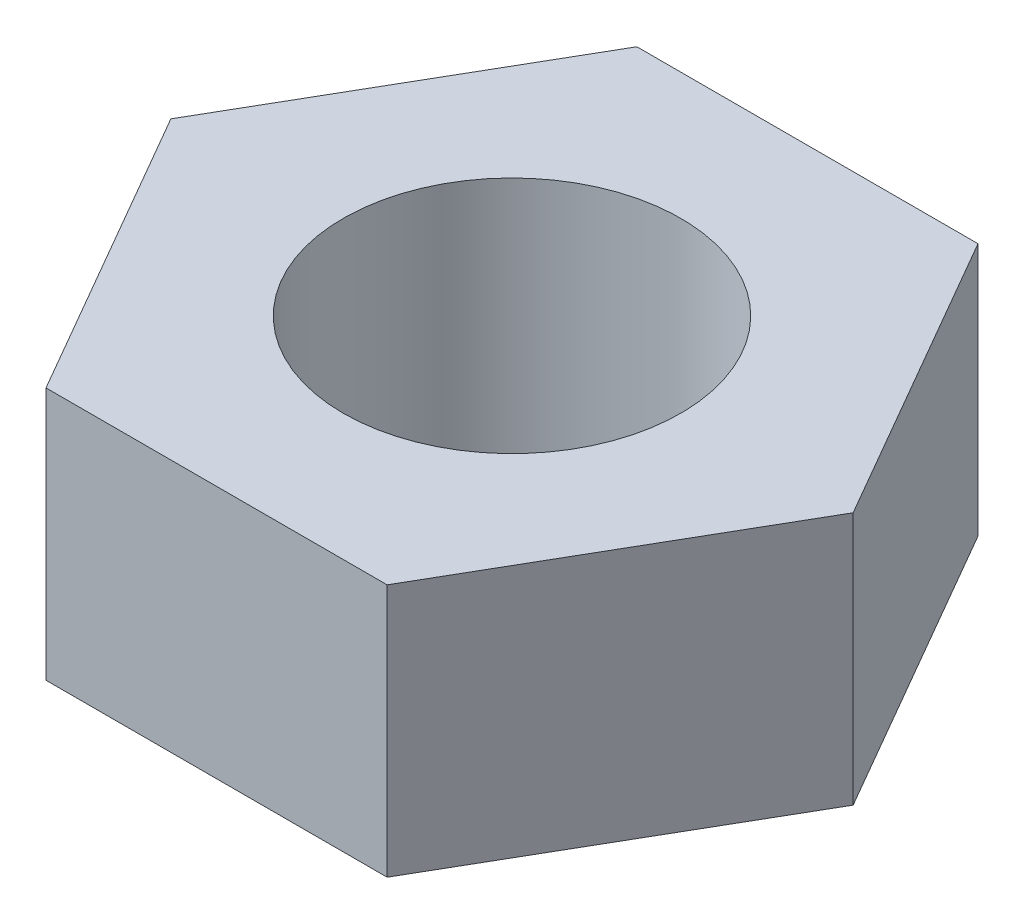
SolidWorks part; units mm, degrees
ref_plane "Front Plane" through (0, 0, 0) normal (0, 0, 1) x (1, 0, 0)
ref_plane "Top Plane" through (0, 0, 0) normal (0, 1, 0) x (1, 0, 0)
ref_plane "Right Plane" through (0, 0, 0) normal (1, 0, 0) x (0, 0, -1)
sketch "Sketch1" plane through (0, 0, 0) normal (0, 1, 0) x (1, 0, 0)
  line L1 (4.0415, 0) -> (2.0207, 3.5)
  line L2 (2.0207, 3.5) -> (-2.0207, 3.5)
  line L3 (-2.0207, 3.5) -> (-4.0415, 0)
  line L4 (-4.0415, 0) -> (-2.0207, -3.5)
  line L5 (-2.0207, -3.5) -> (2.0207, -3.5)
  line L6 (2.0207, -3.5) -> (4.0415, 0)
  circle A0 centre (0, 0) radius 3.5 construction
  circle A1 centre (0, 0) radius 2
  dimension "D2" = 4
  dimension "D1" = 7
extrude "Boss-Extrude1" add sketch "Sketch1" along normal blind 3
